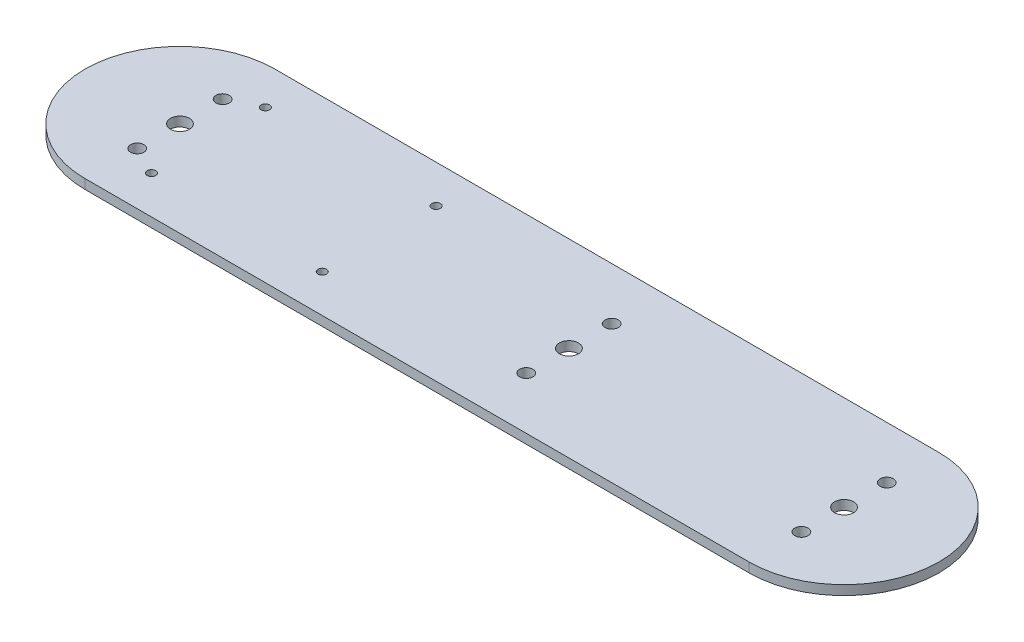
SolidWorks part; units mm, degrees
ref_plane "Front Plane" through (0, 0, 0) normal (0, 0, 1) x (1, 0, 0)
ref_plane "Top Plane" through (0, 0, 0) normal (0, 1, 0) x (1, 0, 0)
ref_plane "Right Plane" through (0, 0, 0) normal (1, 0, 0) x (0, 0, -1)
sketch "Sketch1" plane through (0, 0, 0) normal (0, 1, 0) x (1, 0, 0)
  line L0 (0, 0) -> (350, 0) construction
  line L1 (0, 50) -> (350, 50)
  line L2 (0, -50) -> (350, -50)
  circle A0 centre (0, 0) radius 5
  arc A1 (0, 50) -> (0, -50) centre (0, 0) ccw
  arc A2 (350, -50) -> (350, 50) centre (350, 0) ccw
  circle A3 centre (350, 0) radius 5
  circle A4 centre (0, 22.5) radius 3.5
  circle A5 centre (350, 22.5) radius 3.5
  circle A6 centre (350, -22.5) radius 3.5
  circle A7 centre (0, -22.5) radius 3.5
  dimension "D1" = 10
  dimension "D2" = 100
  dimension "D4" = 100
  dimension "D5" = 10
  dimension "D6" = 7
  dimension "D3" = 350
  dimension "D7" = 22.5
extrude "Boss-Extrude1" add sketch "Sketch1" along normal blind 5 contours L1 A2 L2 A1
sketch "Sketch2" plane through (0, 5, 0) normal (0, 1, 0) x (1, 0, 0)
  line L0 (15, 0) -> (0, 0) construction
  line L1 (15, 30) -> (105, 30) construction
  line L2 (15, 30) -> (15, -30) construction
  line L3 (15, -30) -> (105, -30) construction
  line L4 (105, 30) -> (105, -30) construction
  line L5 (15, 30) -> (105, -30) construction
  line L6 (350, 22.5) -> (205, 22.5) construction
  line L11 (25, -35) -> (95, 35) construction
  line L12 (25, 35) -> (95, -35) construction
  line L13 (350, -22.5) -> (205, -22.5) construction
  circle A0 centre (205, 22.5) radius 3.5
  circle A2 centre (15, -30) radius 2.25
  circle A3 centre (105, -30) radius 2.25
  circle A4 centre (105, 30) radius 2.25
  circle A5 centre (15, 30) radius 2.25
  circle A7 centre (205, 0) radius 5 construction
  circle A8 centre (205, 0) radius 5
  circle A9 centre (205, -22.5) radius 3.5
  circle A10 centre (350, 22.5) radius 3.5 construction
  point P1 (60, 0)
  dimension "D4" = 2
  dimension "D6" = 70
  dimension "D1" = 60
  dimension "D2" = 90
  dimension "D3" = 15
  dimension "D7" = 70
  dimension "D5" = 2
extrude "Cut-Extrude1" cut sketch "Sketch2" against normal blind 5
sketch "Sketch3" [suppressed] plane through (0, 5, 0) normal (0, 1, 0) x (1, 0, 0)
  line L0 (15, 30) -> (105, -30) construction
  line L2 (25, -35) -> (95, -35)
  line L3 (25, -35) -> (25, 35)
  line L4 (25, 35) -> (95, 35)
  line L5 (95, -35) -> (95, 35)
  line L6 (25, -35) -> (95, 35) construction
  line L7 (25, 35) -> (95, -35) construction
  point P4 (60, 0)
  dimension "D1" = 70
  dimension "D2" = 70
extrude "Cut-Extrude2" [suppressed] cut sketch "Sketch3" against normal blind 20
